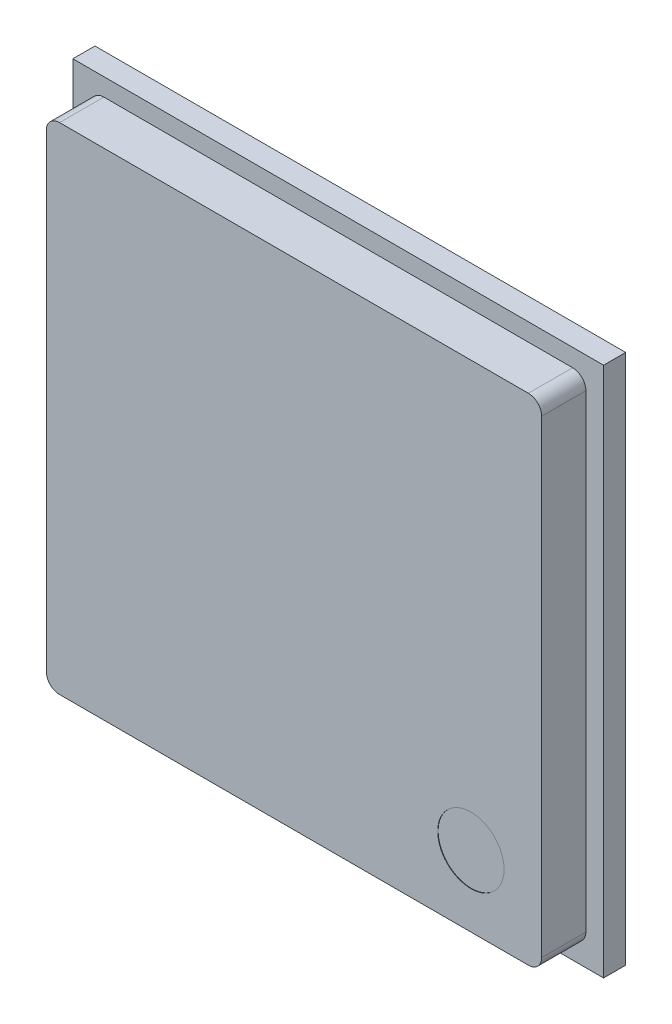
SolidWorks part; units mm, degrees
ref_plane "Plan de face" through (0, 0, 0) normal (0, 0, 1) x (1, 0, 0)
ref_plane "Plan de dessus" through (0, 0, 0) normal (0, 1, 0) x (1, 0, 0)
ref_plane "Plan de droite" through (0, 0, 0) normal (1, 0, 0) x (0, 0, -1)
sketch "Esquisse1" plane through (0, 0, 0) normal (0, 0, 1) x (1, 0, 0)
  line L1 (0, 0) -> (12, 0)
  line L2 (0, 0) -> (0, -12)
  line L3 (0, -12) -> (12, -12)
  line L4 (12, 0) -> (12, -12)
  dimension "D1" = 12
  dimension "D2" = 12
extrude "Boss.-Extru.1" add sketch "Esquisse1" along normal blind 0.5
sketch "Esquisse2" plane through (0, 0, 0.5) normal (0, 0, 1) x (1, 0, 0)
  line L0 (0, 0) -> (0, -12) construction
  line L1 (0.4, -0.4) -> (11.6, -0.4)
  line L2 (0.4, -0.4) -> (0.4, -11.6)
  line L3 (0.4, -11.6) -> (11.6, -11.6)
  line L4 (11.6, -0.4) -> (11.6, -11.6)
  line L5 (12, 0) -> (0, 0) construction
  line L6 (12, -12) -> (12, 0) construction
  line L7 (0, -12) -> (12, -12) construction
  dimension "D1" = 0.4
  dimension "D2" = 0.4
  dimension "D3" = 0.4
  dimension "D4" = 0.4
extrude "Boss.-Extru.2" add sketch "Esquisse2" along normal blind 1
fillet "Congé1" radius 0.3 4 edges at (0.4, -0.4, 1) (11.6, -0.4, 1) (11.6, -11.6, 1) (0.4, -11.6, 1)
sketch "Esquisse3" plane through (0, 0, 1.5) normal (0, 0, 1) x (1, 0, 0)
  line L0 (12, -12) -> (12, 0) construction
  line L1 (0, -12) -> (12, -12) construction
  circle A0 centre (10, -10) radius 0.75
  dimension "D1" = 1.5
  dimension "D2" = 2
  dimension "D3" = 2
extrude "Enlèv. mat.-Extru.1" cut sketch "Esquisse3" against normal blind 0.01
sketch "Esquisse4" plane through (0, 0, 1.5) normal (0, 0, 1) x (1, 0, 0)
  line L0 (11.6, -8.6) -> (0.4, -8.6)
  line L1 (11.6, -11.3) -> (11.6, -0.7) construction
  line L2 (0.4, -0.7) -> (0.4, -11.3) construction
  line L3 (0.7, -11.6) -> (11.3, -11.6) construction
  text T0 "AP6212A" font "Century Gothic" height in points 4
  dimension "D1" = 3
